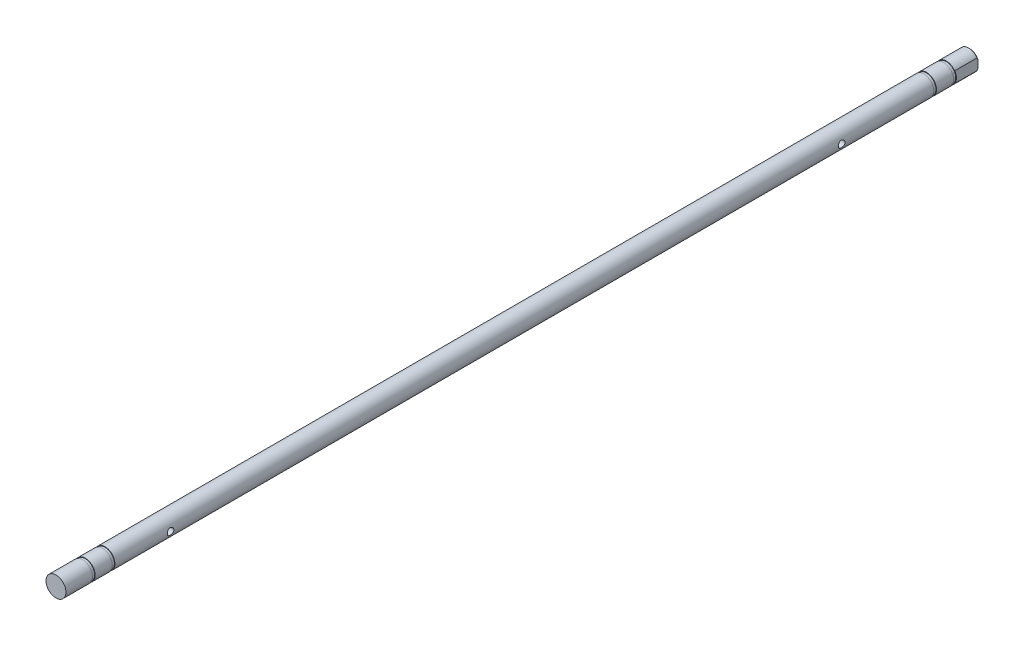
SolidWorks part; units mm, degrees
material "AISI 4340 Steel, normalized"
ref_plane "Front Plane" through (0, 0, 0) normal (0, 0, 1) x (1, 0, 0)
ref_plane "Top Plane" through (0, 0, 0) normal (0, 1, 0) x (1, 0, 0)
ref_plane "Right Plane" through (0, 0, 0) normal (1, 0, 0) x (0, 0, -1)
sketch "Sketch1" plane through (0, 0, 0) normal (0, 0, 1) x (1, 0, 0)
  circle A0 centre (0, 0) radius 3
extrude "Boss-Extrude1" add sketch "Sketch1" along normal blind 275
sketch "Sketch3" plane through (0, 0, 0) normal (1, 0, 0) x (0, 0, -1)
  line L0 (0, 3) -> (-275, 3) construction
  line L1 (-267, 3) -> (-266.2, 3)
  line L2 (-267, 3) -> (-267, 2.5)
  line L3 (-267, 2.5) -> (-266.2, 2.5)
  line L4 (-266.2, 3) -> (-266.2, 2.5)
  line L5 (-275, 3) -> (-275, -3) construction
  line L6 (-263.365, 0) -> (-260, 0) construction
  line L7 (-261.05, 3) -> (-260.25, 3)
  line L8 (-261.05, 3) -> (-261.05, 2.5)
  line L9 (-261.05, 2.5) -> (-260.25, 2.5)
  line L10 (-260.25, 3) -> (-260.25, 2.5)
  line L11 (-13.8, 3) -> (-13, 3)
  line L12 (-13.8, 3) -> (-13.8, 2.5)
  line L13 (-13.8, 2.5) -> (-13, 2.5)
  line L14 (-13, 3) -> (-13, 2.5)
  line L15 (-7.85, 3) -> (-7.05, 3)
  line L16 (-7.85, 3) -> (-7.85, 2.5)
  line L17 (-7.85, 2.5) -> (-7.05, 2.5)
  line L18 (-7.05, 3) -> (-7.05, 2.5)
  point P12 (-260.65, 2.5)
  point P21 (-7.05, 2.75)
  dimension "D1" = 0.8
  dimension "D2" = 0.5
  dimension "D3" = 8
  dimension "D4" = 0.5
  dimension "D5" = 0.8
  dimension "D6" = 13.95
  dimension "D7" = 5.15
  dimension "D8" = 0.5
  dimension "D9" = 0.8
  dimension "D10" = 0.5
  dimension "D11" = 0.8
  dimension "D12" = 5.15
  dimension "D13" = 261.2
revolve "Cut-Revolve1" cut sketch "Sketch3" angle 360 about L6
sketch "Sketch4" plane through (0, 0, 0) normal (0, 1, 0) x (1, 0, 0)
  line L0 (0, 6.9099) -> (0, -272.7358) construction
  line L1 (3, 0) -> (-3, 0) construction
  line L2 (2.5, 0) -> (5.9701, 0)
  line L3 (2.5, 0) -> (2.5, -7)
  line L4 (2.5, -7) -> (5.9701, -7)
  line L5 (5.9701, 0) -> (5.9701, -7)
  line L6 (-5.4253, 0) -> (-2.5, 0)
  line L7 (-5.4253, 0) -> (-5.4253, -7)
  line L8 (-5.4253, -7) -> (-2.5, -7)
  line L9 (-2.5, 0) -> (-2.5, -7)
  line L10 (3, -7.05) -> (3, 0) construction
  line L11 (-3, 0) -> (-3, -7.05) construction
  dimension "D1" = 7
  dimension "D2" = 0.5
  dimension "D3" = 0.5
extrude "Cut-Extrude2" cut sketch "Sketch4" against normal through all both and the other way through all
chamfer "Chamfer1" distance 0.3 angle 45 2 edges at (0, -3, 0) (0, 3, 0)
sketch "Sketch5" plane through (0, 0, 0) normal (0, 0, 1) x (1, 0, 0)
  circle A0 centre (0, 0) radius 2.85
  circle A1 centre (0, 0) radius 2.49
extrude "Retaining_Grooves_D5p7_1" add sketch "Sketch5" along normal blind 0.8 from offset 7.05
sketch "Sketch6" plane through (0, 0, 0) normal (0, 0, 1) x (1, 0, 0)
  circle A0 centre (0, 0) radius 2.85
  circle A1 centre (0, 0) radius 2.49
extrude "Retaining_Grooves_D5p7_2" add sketch "Sketch6" along normal blind 0.8 from offset 13
sketch "Sketch7" plane through (0, 0, 0) normal (0, 0, 1) x (1, 0, 0)
  circle A0 centre (0, 0) radius 2.85
  circle A1 centre (0, 0) radius 2.49
extrude "Retaining_Grooves_D5p7_3" add sketch "Sketch7" along normal blind 0.8 from offset 260.25
sketch "Sketch8" plane through (0, 0, 0) normal (0, 0, 1) x (1, 0, 0)
  circle A0 centre (0, 0) radius 2.85
  circle A1 centre (0, 0) radius 2.49
extrude "Retaining_Grooves_D5p7_4" add sketch "Sketch8" along normal blind 0.8 from offset 266.2
sketch "Sketch9" plane through (0, 0, 0) normal (1, 0, 0) x (0, 0, -1)
  circle A0 centre (-41.5, 0) radius 1
  circle A1 centre (-243.5, 0) radius 1
extrude "Two_Hub_Cross_Pin_D2" cut sketch "Sketch9" against normal through all and the other way through all
